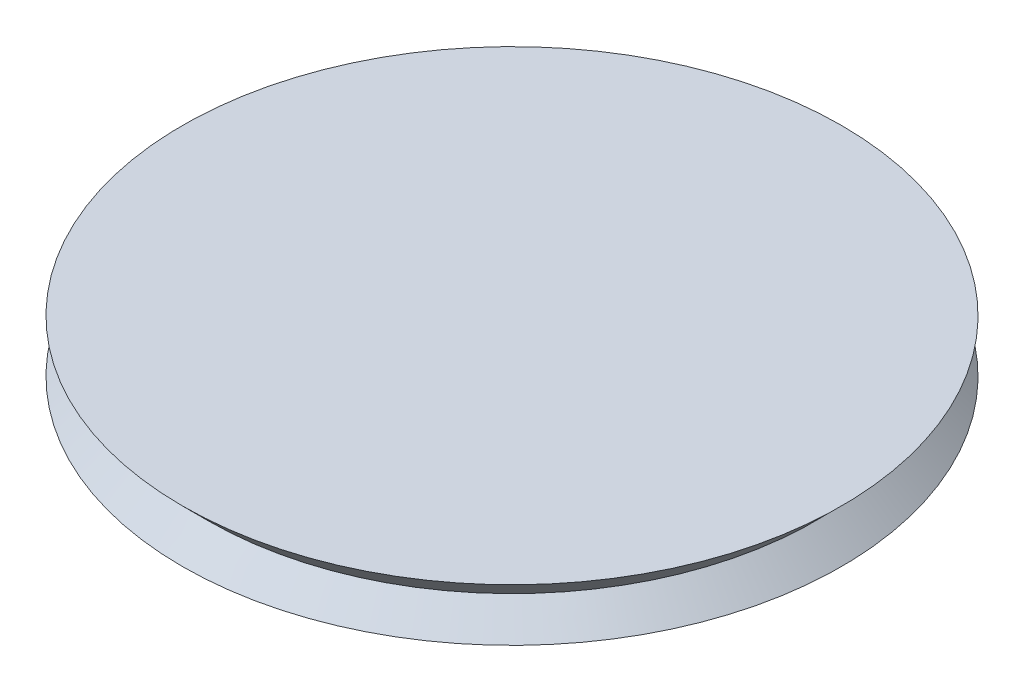
SolidWorks part; units mm, degrees
ref_plane "Front Plane" through (0, 0, 0) normal (0, 0, 1) x (1, 0, 0)
ref_plane "Top Plane" through (0, 0, 0) normal (0, 1, 0) x (1, 0, 0)
ref_plane "Right Plane" through (0, 0, 0) normal (1, 0, 0) x (0, 0, -1)
sketch "Sketch1" plane through (0, 0, 0) normal (0, 1, 0) x (1, 0, 0)
  line L0 (0, 6.1) -> (-6.1, 6.1)
  line L1 (-6.1, 6.1) -> (-6.1, 0)
  line L2 (-6.1, 0) -> (-6.1, -6.1)
  line L3 (-6.1, -6.1) -> (0, -6.1)
  circle A0 centre (0, 0) radius 1.6
  circle A1 centre (0, 0) radius 6.1
  dimension "D1" = 3.2
  dimension "D2" = 4.5
extrude "Boss-Extrude1" add sketch "Sketch1" along normal blind 7.4 contours A1 A0 | A1 L2 L3 | A1 L0 L1
sketch "Sketch2" plane through (-6.1, 0, 0) normal (-1, 0, 0) x (0, 0, 1)
  line L0 (0, 7.4) -> (0, 0) construction
  line L1 (-6.1, 7.4) -> (6.1, 7.4) construction
  circle A0 centre (0, 3.7) radius 1.8
  dimension "D1" = 3.6
extrude "Cut-Extrude2" cut sketch "Sketch2" against normal blind 4
sketch "Sketch3" plane through (-2.1, 0, 0) normal (-1, 0, 0) x (0, 0, 1)
  circle A0 centre (0, 3.7) radius 1.2
  dimension "D1" = 2.4
extrude "Cut-Extrude3" cut sketch "Sketch3" against normal blind 1
sketch "Sketch4" plane through (0, 7.4, 0) normal (0, 1, 0) x (1, 0, 0)
  circle A0 centre (0, 0) radius 52.225
  dimension "D1" = 104.45
extrude "Boss-Extrude2" add sketch "Sketch4" along normal blind 8
sketch "Sketch6" plane through (0, 0, 0) normal (1, 0, 0) x (0, 0, -1)
  line L1 (-52.225, 15.4) -> (-52.225, 7.4) construction
  line L3 (-52.225, 11.4) -> (52.225, 11.4) construction
  line L4 (52.225, 7.4) -> (52.225, 15.4) construction
  line L8 (-46.225, 11.4) -> (-50.225, 7.4)
  line L9 (-46.225, 7.4) -> (-50.225, 7.4) construction
  line L10 (-46.225, 15.4) -> (-46.225, 7.4) construction
  line L11 (-52.225, 7.4) -> (52.225, 7.4) construction
  line L12 (-46.225, 15.4) -> (-50.225, 15.4) construction
  line L13 (-46.225, 11.4) -> (-50.225, 15.4)
  line L14 (-50.225, 15.4) -> (-52.225, 15.4)
  line L15 (-52.225, 15.4) -> (-52.225, 7.4)
  line L16 (-52.225, 7.4) -> (-50.225, 7.4)
  line L17 (0, 0) -> (0, 11.4) construction
  dimension "D1" = 45
  dimension "D2" = 2
revolve "Cut-Revolve1" cut sketch "Sketch6" angle 360 about L17
fillet "Fillet1" radius 1 4 edges at (-3.05, 7.4, -6.1) (6.1, 7.4, 0) (-6.1, 7.4, 0) (-3.05, 7.4, 6.1)
